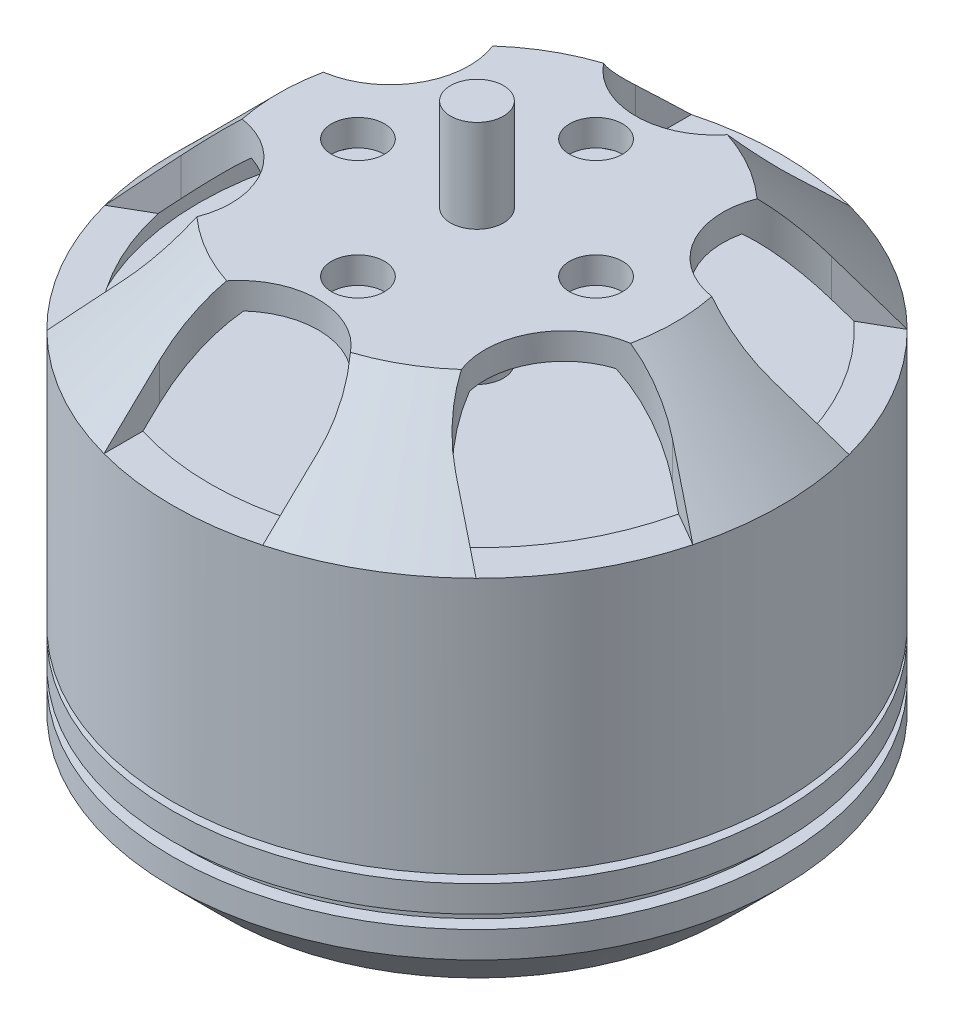
SolidWorks part; units mm, degrees
ref_plane "Front Plane" through (0, 0, 0) normal (0, 0, 1) x (1, 0, 0)
ref_plane "Top Plane" through (0, 0, 0) normal (0, 1, 0) x (1, 0, 0)
ref_plane "Right Plane" through (0, 0, 0) normal (1, 0, 0) x (0, 0, -1)
sketch "Sketch1" plane through (0, 0, 0) normal (0, 0, 1) x (1, 0, 0)
  line L0 (0, 22) -> (0, -1.8)
  line L1 (0, -1.8) -> (1, -1.8)
  line L2 (1, -1.8) -> (1, 0)
  line L3 (1, 0) -> (9.5, 0)
  line L4 (9.5, 0) -> (11.5, 2)
  line L5 (11.5, 2) -> (11.5, 3)
  line L6 (11.5, 14.5) -> (7.5, 18.5)
  line L7 (7.5, 18.5) -> (1, 18.5)
  line L8 (1, 18.5) -> (1, 22)
  line L9 (1, 22) -> (0, 22)
  line L11 (1, 16.5) -> (1, 13.4192)
  line L12 (1, 13.4192) -> (10.5, 13.4192)
  line L13 (10.5, 13.4192) -> (10.5, 14.0858)
  line L14 (10.5, 14.0858) -> (7.0858, 17.5)
  line L15 (7.0858, 17.5) -> (2, 17.5)
  line L16 (2, 17.5) -> (2, 16.5)
  line L17 (2, 16.5) -> (1, 16.5)
  line L18 (11.5, 4.8) -> (11.5, 14.5)
  line L19 (11.5, 3) -> (11, 3)
  line L21 (11.5, 3.5) -> (11, 3.5)
  line L22 (11, 3) -> (11, 3.5)
  line L23 (11.5, 4.5) -> (9.5, 4.5)
  line L25 (11.5, 4.8) -> (9.5, 4.8)
  line L26 (9.5, 4.5) -> (9.5, 4.8)
  line L27 (11.5, 3.5) -> (11.5, 4.5)
  point P13 (10.5, 13.7525)
  dimension "D1" = 23.8
  dimension "D2" = 1.8
  dimension "D3" = 45
  dimension "D4" = 2
  dimension "D5" = 1
  dimension "D6" = 1
  dimension "D7" = 3.5
  dimension "D8" = 45
  dimension "D9" = 11.5
  dimension "D10" = 4
  dimension "D11" = 1
  dimension "D12" = 1
  dimension "D13" = 1
  dimension "D14" = 1
  dimension "D15" = 1
  dimension "D16" = 1
  dimension "D17" = 1
  dimension "D18" = 0.5
  dimension "D19" = 0.5
  dimension "D20" = 2
  dimension "D21" = 0.3
revolve "Revolve1" add sketch "Sketch1" angle 360 about L0
sketch "Sketch2" plane through (0, 18.5, 0) normal (0, 1, 0) x (1, 0, 0)
  line L0 (-3, 9) -> (-3, 13.1523)
  line L1 (-3, 13.1523) -> (3, 13.1523)
  line L2 (3, 13.1523) -> (3, 9)
  line L3 (12.8902, 3.9781) -> (9.2942, 1.9019)
  line L4 (6.2942, 7.0981) -> (9.8902, 9.1742)
  line L5 (9.8902, 9.1742) -> (12.8902, 3.9781)
  line L6 (9.8902, -9.1742) -> (6.2942, -7.0981)
  line L7 (9.2942, -1.9019) -> (12.8902, -3.9781)
  line L8 (12.8902, -3.9781) -> (9.8902, -9.1742)
  line L9 (-3, -13.1523) -> (-3, -9)
  line L10 (3, -9) -> (3, -13.1523)
  line L11 (3, -13.1523) -> (-3, -13.1523)
  line L12 (-12.8902, -3.9781) -> (-9.2942, -1.9019)
  line L13 (-6.2942, -7.0981) -> (-9.8902, -9.1742)
  line L14 (-9.8902, -9.1742) -> (-12.8902, -3.9781)
  line L15 (-9.8902, 9.1742) -> (-6.2942, 7.0981)
  line L16 (-9.2942, 1.9019) -> (-12.8902, 3.9781)
  line L17 (-12.8902, 3.9781) -> (-9.8902, 9.1742)
  circle A0 centre (0, 0) radius 4.5 construction
  circle A1 centre (0, 0) radius 9 construction
  circle A2 centre (0, 4.5) radius 1
  arc A3 (-3, 9) -> (3, 9) centre (0, 9) ccw
  arc A4 (6.2942, 7.0981) -> (9.2942, 1.9019) centre (7.7942, 4.5) ccw
  arc A5 (9.2942, -1.9019) -> (6.2942, -7.0981) centre (7.7942, -4.5) ccw
  arc A6 (3, -9) -> (-3, -9) centre (0, -9) ccw
  arc A7 (-6.2942, -7.0981) -> (-9.2942, -1.9019) centre (-7.7942, -4.5) ccw
  arc A8 (-9.2942, 1.9019) -> (-6.2942, 7.0981) centre (-7.7942, 4.5) ccw
  circle A9 centre (4.5, 0) radius 1
  circle A10 centre (0, -4.5) radius 1
  circle A11 centre (-4.5, 0) radius 1
  dimension "D1" = 9
  dimension "D2" = 18
  dimension "D3" = 2
  dimension "D4" = 6
  dimension "D5" = 6
  dimension "D6" = 4
extrude "Cut-Extrude1" cut sketch "Sketch2" against normal blind 4
sketch "Sketch3" [suppressed] plane through (0, 0, 0) normal (0, -1, 0) x (1, 0, 0)
  circle A0 centre (0, 0) radius 6 construction
  circle A1 centre (0, 0) radius 8 construction
  circle A2 centre (0, 6) radius 1
  circle A3 centre (-6, 0) radius 1
  circle A4 centre (0, -6) radius 1
  circle A5 centre (6, 0) radius 1
  dimension "D1" = 12
  dimension "D2" = 16
  dimension "D3" = 2
extrude "Cut-Extrude2" [suppressed] cut sketch "Sketch3" against normal blind 3
sketch "Sketch4" plane through (0, 0, 0) normal (0, -1, 0) x (1, 0, 0)
  circle A0 centre (0, 0) radius 6 construction
  circle A1 centre (0, 0) radius 8 construction
  circle A2 centre (0, 6) radius 1
  circle A3 centre (0, -6) radius 1
  circle A4 centre (-8, 0) radius 1
  circle A5 centre (8, 0) radius 1
  dimension "D1" = 16
  dimension "D2" = 12
  dimension "D3" = 2
extrude "Cut-Extrude3" cut sketch "Sketch4" against normal blind 3
